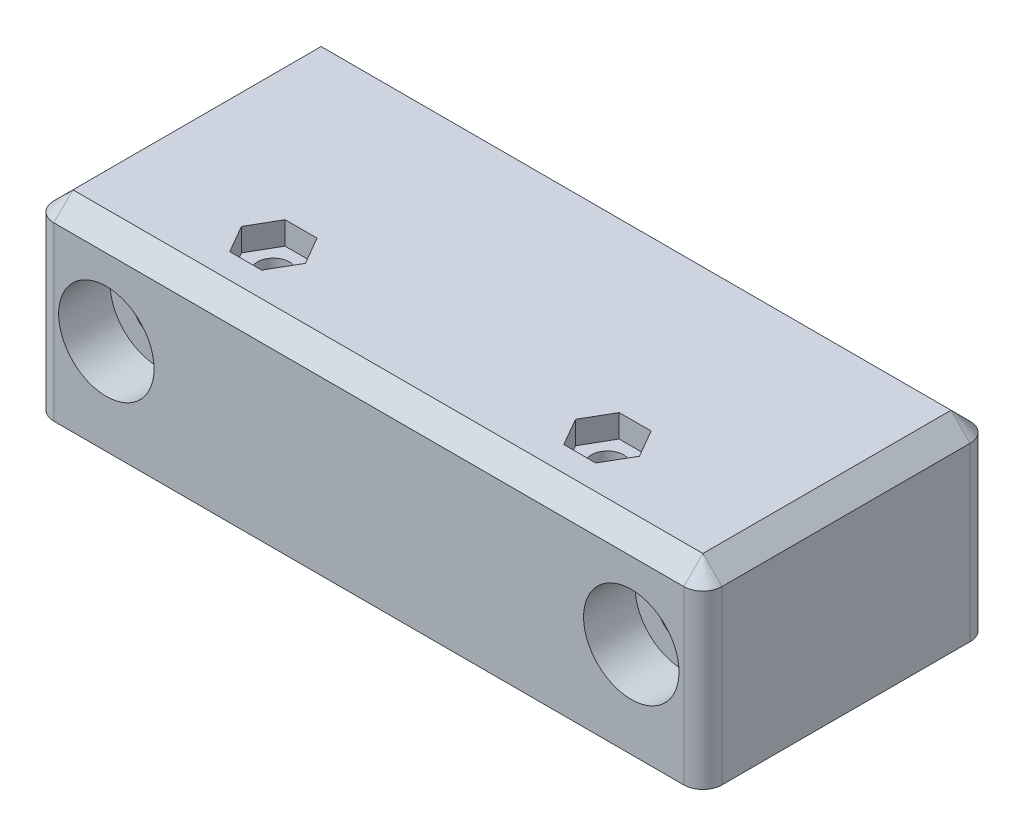
SolidWorks part; units mm, degrees
ref_plane "Front Plane" through (0, 0, 0) normal (0, 0, 1) x (1, 0, 0)
ref_plane "Top Plane" through (0, 0, 0) normal (0, 1, 0) x (1, 0, 0)
ref_plane "Right Plane" through (0, 0, 0) normal (1, 0, 0) x (0, 0, -1)
ref_plane "Top of Part Plane" through (0, 20, 0) normal (0, 1, 0) x (1, 0, 0)
ref_plane "FrontOfPartPlane" through (0, 0, 15) normal (0, 0, 1) x (1, 0, 0)
sketch "Main Block Sketch" plane through (0, 0, 0) normal (0, 1, 0) x (1, 0, 0)
  line L5 (-35, 0) -> (35, 0)
  line L6 (-35, -30) -> (35, -30)
  line L7 (-35, -30) -> (-35, 0)
  line L9 (-17.5, -22.5) -> (17.5, -22.5) construction
  line L12 (35, -30) -> (35, 0)
  point P0 (0, 0)
  point P4 (0, -22.5)
  dimension "D1" = 70
  dimension "D2" = 35
  dimension "D3" = 30
  dimension "D4" = 22.5
extrude "Main Block" add sketch "Main Block Sketch" along normal up to surface (20 mm away) up to plane "Top of Part Plane"
sketch "Nut TrapsSketch" plane through (0, 20, 0) normal (0, 1, 0) x (1, 0, 0)
  line L2 (-15.8257, -19.6) -> (-19.1743, -19.6)
  line L3 (-19.1743, -19.6) -> (-20.8486, -22.5)
  line L4 (-20.8486, -22.5) -> (-19.1743, -25.4)
  line L5 (-19.1743, -25.4) -> (-15.8257, -25.4)
  line L6 (-15.8257, -25.4) -> (-14.1514, -22.5)
  line L7 (-14.1514, -22.5) -> (-15.8257, -19.6)
  line L8 (19.1743, -19.6) -> (15.8257, -19.6)
  line L9 (15.8257, -19.6) -> (14.1514, -22.5)
  line L10 (14.1514, -22.5) -> (15.8257, -25.4)
  line L11 (15.8257, -25.4) -> (19.1743, -25.4)
  line L12 (19.1743, -25.4) -> (20.8486, -22.5)
  line L13 (20.8486, -22.5) -> (19.1743, -19.6)
  circle A0 centre (-17.5, -22.5) radius 2.9 construction
  circle A1 centre (17.5, -22.5) radius 2.9 construction
  point P4 (0, 0)
  dimension "D2" = 5.8
extrude "Nut Traps" cut sketch "Nut TrapsSketch" against normal blind 2.4
hole_wizard "Tension Screw Holes" positions "Sketch3" profile "Sketch4" hole size "M3" standard "ANSI Metric" end condition through all
sketch "Sketch3" plane through (0, 20, 0) normal (0, 1, 0) x (1, 0, 0)
  point P0 (-17.5, -22.5)
  point P3 (17.5, -22.5)
sketch "Sketch4" plane through (-17.5, 20, 22.5) normal (1, 0, 0) x (0, 0, 1)
  line L0 (0, 0) -> (0, 20)
  line L1 (0, 20) -> (1.7, 20)
  line L2 (1.7, 20) -> (1.7, 0)
  line L5 (1.7, 0) -> (0, 0)
  line L11 (0, -6.35) -> (0, 107.95) construction
  dimension "Thru Hole Dia." = 3.4
  dimension "Thru Hole Depth" = 20
sketch "Mounting Screw Holes Positions" plane through (0, 0, 15) normal (0, 0, 1) x (1, 0, 0)
  line L0 (-27.5, 10) -> (27.5, 10) construction
  point P3 (0, 10)
  dimension "D1" = 10
  dimension "D2" = 55
hole_wizard "CBORE for M5 Hex Socket Head Cap Screw1" positions "Sketch6" profile "Sketch7" counterbore size "M5" standard "ISO" end condition through all
sketch "Sketch6" plane through (0, 0, 30) normal (0, 0, 1) x (1, 0, 0)
  point P0 (-27.5, 10)
  point P3 (27.5, 10)
sketch "Sketch7" plane through (-27.5, 10, 30) normal (1, 0, 0) x (0, -1, 0)
  line L0 (0, 0) -> (0, 30)
  line L1 (0, 30) -> (2.75, 30)
  line L3 (2.75, 30) -> (2.75, 5.4)
  line L4 (2.75, 5.4) -> (5, 5.4)
  line L5 (5, 5.4) -> (5, 0)
  line L7 (5, 0) -> (0, 0)
  line L11 (0, -6.35) -> (0, 107.95) construction
  dimension "Thru Hole Dia." = 5.5
  dimension "Thru Hole Depth" = 30
  dimension "C'Bore Dia." = 10
  dimension "C'Bore Depth" = 5.4
fillet "Print Helper Fillets" radius 2 4 edges at (35, 10, 30) (35, 10, 0) (-35, 10, 0) (-35, 10, 30)
chamfer "Cosmetic Chamfer" distance 2 angle 45 8 edges at (-35, 20, 15) (-34.4142, 20, 29.4142) (-34.4142, 20, 0.5858) (0, 20, 30) (0, 20, 0) (34.4142, 20, 29.4142) (34.4142, 20, 0.5858) (35, 20, 15)
